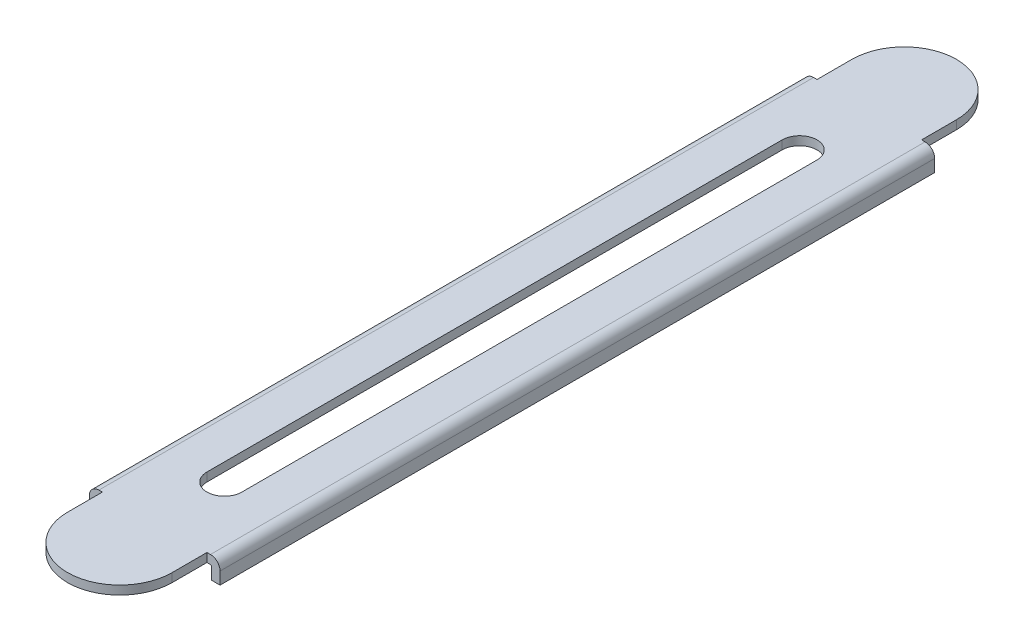
SolidWorks part; units mm, degrees
ref_plane "Alzado" through (0, 0, 0) normal (0, 0, 1) x (1, 0, 0)
ref_plane "Planta" through (0, 0, 0) normal (0, 1, 0) x (1, 0, 0)
ref_plane "Vista lateral" through (0, 0, 0) normal (1, 0, 0) x (0, 0, -1)
ref_plane "Plano1" through (0, 44.7424, 0) normal (0, -1, 0) x (1, 0, 0)
sketch "Croquis1" plane through (0, 44.7424, 0) normal (0, -1, 0) x (1, 0, 0)
  line L0 (20, -96) -> (20, -6)
  line L1 (8, -6) -> (8, -96)
  arc A0 (8, -96) -> (20, -96) centre (14, -96) ccw
  arc A1 (20, -6) -> (8, -6) centre (14, -6) ccw
extrude "Saliente-Extruir1" add sketch "Croquis1" against normal blind 1
sketch "Croquis2" plane through (20, 0, 0) normal (1, 0, 0) x (0, 0, -1)
  line L0 (10, 44.7424) -> (10, 45.7424)
  line L1 (10, 45.7424) -> (92, 45.7424)
  line L2 (92, 45.7424) -> (92, 44.7424)
  line L3 (92, 44.7424) -> (10, 44.7424)
extrude "Saliente-Extruir2" add sketch "Croquis2" along normal blind 1.5
sketch "Croquis3" plane through (0, 44.7424, 0) normal (0, -1, 0) x (1, 0, 0)
  line L0 (21.5, -92) -> (20.5, -92)
  line L1 (20.5, -92) -> (20.5, -10)
  line L2 (20.5, -10) -> (21.5, -10)
  line L3 (21.5, -10) -> (21.5, -92)
extrude "Saliente-Extruir3" add sketch "Croquis3" along normal blind 1.5
sketch "Croquis4" plane through (8, 0, 0) normal (-1, 0, 0) x (0, 0, 1)
  line L0 (-92, 44.7424) -> (-92, 45.7424)
  line L1 (-92, 45.7424) -> (-10, 45.7424)
  line L2 (-10, 45.7424) -> (-10, 44.7424)
  line L3 (-10, 44.7424) -> (-92, 44.7424)
extrude "Saliente-Extruir4" add sketch "Croquis4" along normal blind 1.5
sketch "Croquis5" plane through (0, 44.7424, 0) normal (0, -1, 0) x (1, 0, 0)
  line L0 (7.5, -92) -> (6.5, -92)
  line L1 (6.5, -92) -> (6.5, -10)
  line L2 (6.5, -10) -> (7.5, -10)
  line L3 (7.5, -10) -> (7.5, -92)
extrude "Saliente-Extruir5" add sketch "Croquis5" along normal blind 1.5
sketch "Croquis6" plane through (0, 45.7424, 0) normal (0, 1, 0) x (-1, 0, 0)
  line L0 (-12, -84) -> (-12, -18)
  line L1 (-16, -18) -> (-16, -84)
  arc A0 (-16, -84) -> (-12, -84) centre (-14, -84) ccw
  arc A1 (-12, -18) -> (-16, -18) centre (-14, -18) ccw
extrude "Cortar-Extruir1" cut sketch "Croquis6" against normal through all
ref_plane "Plano2" through (0, 0, -6) normal (0, 0, -1) x (-1, 0, 0)
fillet "Redondeo1" radius 0.1 2 edges at (7.5, 44.7424, -51) (20.5, 44.7424, -51)
fillet "Redondeo2" radius 1.1 2 edges at (6.5, 45.7424, -51) (21.5, 45.7424, -51)
